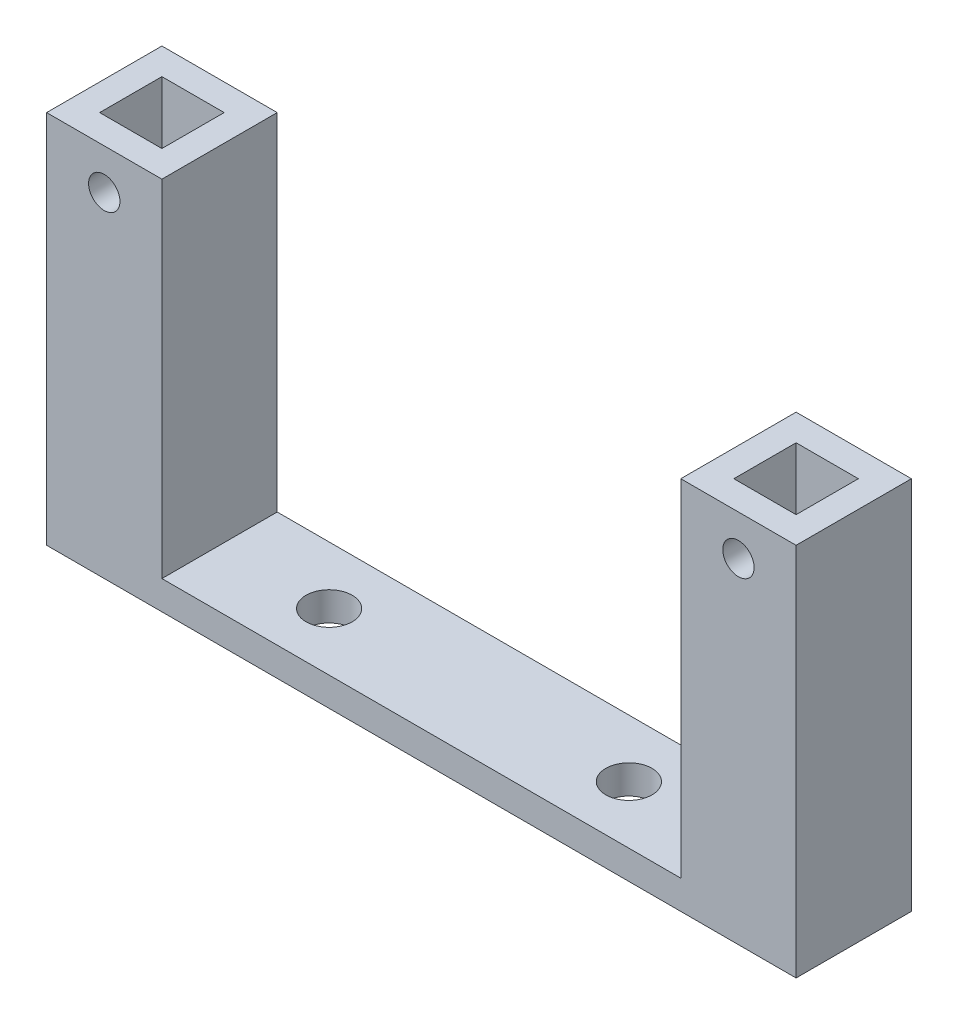
SolidWorks part; units mm, degrees
ref_plane "Front Plane" through (0, 0, 0) normal (0, 0, 1) x (1, 0, 0)
ref_plane "Top Plane" through (0, 0, 0) normal (0, 1, 0) x (1, 0, 0)
ref_plane "Right Plane" through (0, 0, 0) normal (1, 0, 0) x (0, 0, -1)
sketch "Sketch1" plane through (0, 0, 0) normal (0, 1, 0) x (1, 0, 0)
  line L1 (-41.275, 6.35) -> (41.275, 6.35)
  line L2 (-41.275, 6.35) -> (-41.275, -6.35)
  line L3 (-41.275, -6.35) -> (41.275, -6.35)
  line L4 (41.275, 6.35) -> (41.275, -6.35)
extrude "Boss-Extrude1" add sketch "Sketch1" along normal blind 3.175
sketch "Sketch3" plane through (0, 3.175, 0) normal (0, 1, 0) x (1, 0, 0)
  line L0 (-41.275, -6.35) -> (41.275, -6.35) construction
  line L1 (-41.275, 6.35) -> (-28.575, 6.35)
  line L2 (-41.275, 6.35) -> (-41.275, -6.35)
  line L3 (-41.275, -6.35) -> (-28.575, -6.35)
  line L4 (-28.575, 6.35) -> (-28.575, -6.35)
extrude "Boss-Extrude2" add sketch "Sketch3" along normal blind 38.1
sketch "Sketch4" plane through (0, 3.175, 0) normal (0, 1, 0) x (1, 0, 0)
  line L0 (-28.575, -6.35) -> (41.275, -6.35) construction
  line L1 (41.275, 6.35) -> (28.575, 6.35)
  line L2 (41.275, 6.35) -> (41.275, -6.35)
  line L3 (41.275, -6.35) -> (28.575, -6.35)
  line L4 (28.575, 6.35) -> (28.575, -6.35)
extrude "Boss-Extrude3" add sketch "Sketch4" along normal blind 38.1
sketch "Sketch5" plane through (0, 41.275, 0) normal (0, 1, 0) x (1, 0, 0)
  line L1 (-38.354, 3.429) -> (-31.496, 3.429)
  line L2 (-38.354, 3.429) -> (-38.354, -3.429)
  line L3 (-38.354, -3.429) -> (-31.496, -3.429)
  line L4 (-31.496, 3.429) -> (-31.496, -3.429)
extrude "Cut-Extrude1" cut sketch "Sketch5" against normal blind 38.1
sketch "Sketch6" plane through (0, 41.275, 0) normal (0, 1, 0) x (1, 0, 0)
  line L1 (31.496, 3.429) -> (38.354, 3.429)
  line L2 (31.496, 3.429) -> (31.496, -3.429)
  line L3 (31.496, -3.429) -> (38.354, -3.429)
  line L4 (38.354, 3.429) -> (38.354, -3.429)
  point P4 (0, 0)
extrude "Cut-Extrude2" cut sketch "Sketch6" against normal blind 38.1
sketch "Sketch9" plane through (0, 3.175, 0) normal (0, 1, 0) x (1, 0, 0)
  circle A0 centre (-16.51, 0) radius 2.54
  circle A1 centre (16.51, 0) radius 2.54
extrude "Cut-Extrude3" cut sketch "Sketch9" against normal blind 38.1
sketch "Sketch10" plane through (0, 41.275, 0) normal (0, 1, 0) x (1, 0, 0)
hole_wizard "#8-32 Tapped Hole2" positions "3DSketch2" profile "Sketch11" tap size "#8-32" standard "ANSI Inch"
sketch3d "3DSketch2"
  point P0 (-34.925, 36.83, 6.35)
  point P2 (34.925, 36.83, 6.35)
  point P5 (0, 0, 0)
  point P6 (0, 0, 0)
  point P7 (0, 0, 0)
sketch "Sketch11" plane through (-34.925, 36.83, 6.35) normal (1, 0, 0) x (0, -1, 0)
  line L0 (0, 0) -> (0, 2.921)
  line L1 (0, 2.921) -> (1.7272, 2.921)
  line L2 (1.7272, 2.921) -> (1.7272, 0)
  line L5 (1.7272, 0) -> (0, 0)
  line L11 (0, -6.35) -> (0, 107.95) construction
  dimension "Thru Tap Drill Dia." = 3.4544
  dimension "Thru Tap Drill Depth" = 2.921
cosmetic thread "Hole Thread3" parameters "D2"=4.1656
cosmetic thread "Hole Thread4" parameters "D2"=4.1656
